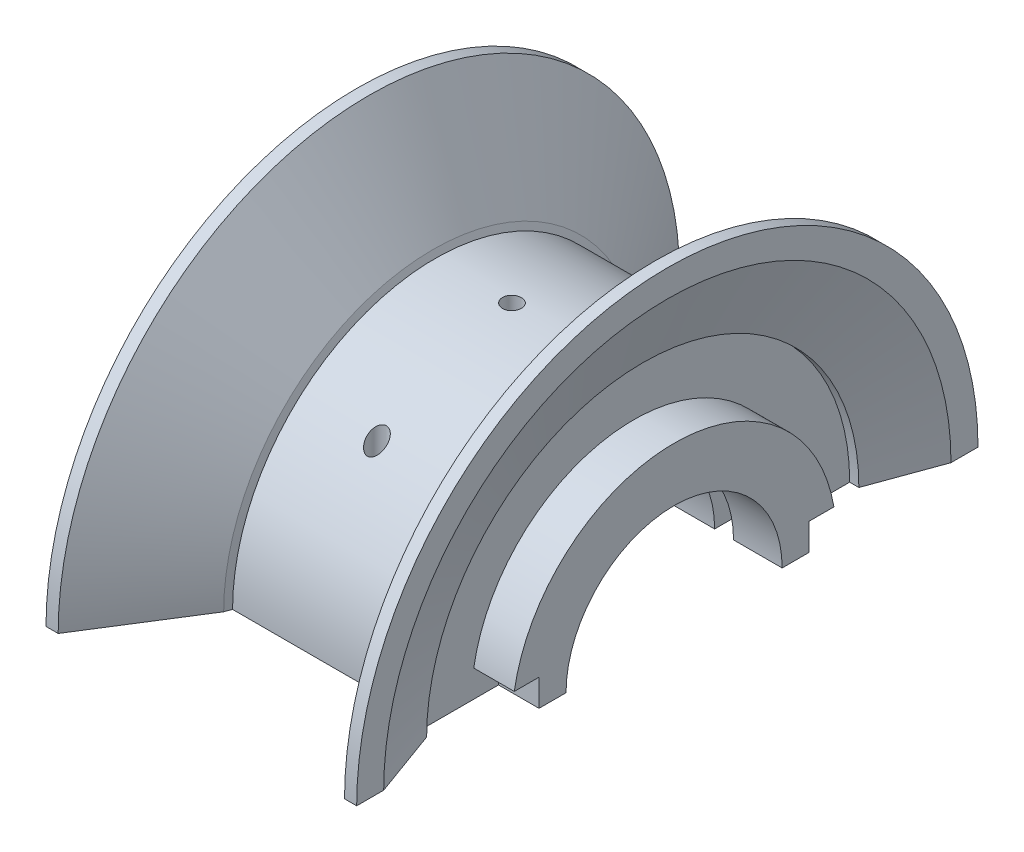
SolidWorks part; units mm, degrees
other "DifferReelB"
material "Nylon 101"
ref_plane "Front" through (0, 0, 0) normal (0, 0, 1) x (1, 0, 0)
ref_plane "Top" through (0, 0, 0) normal (0, 1, 0) x (1, 0, 0)
ref_plane "Right" through (0, 0, 0) normal (1, 0, 0) x (0, 0, -1)
sketch "BodySke" plane through (0, 0, 0) normal (0, 1, 0) x (1, 0, 0)
  line L0 (4.5, 0) -> (4.5, 11.5)
  line L1 (4.5, 11.5) -> (4.3, 11.5)
  line L2 (4.3, 11.5) -> (2.2982, 6)
  line L3 (2.2982, 6) -> (-2.2982, 6)
  line L4 (-2.2982, 6) -> (-4.3, 11.5)
  line L5 (-4.3, 11.5) -> (-4.5, 11.5)
  line L6 (-4.5, 11.5) -> (-4.5, 0)
  line L7 (-4.5, 0) -> (4.5, 0)
  point P2 (0, 0)
  point P9 (0, 6)
  dimension "D1" = 0.2
  dimension "D2" = 6
  dimension "D3" = 70
  dimension "D4" = 11.5
  dimension "D5" = 9
revolve "Body" add sketch "BodySke" angle 360 about L7
sketch "BoldSke" plane through (0, 0, 0) normal (0, 1, 0) x (1, 0, 0)
  line L0 (-2.2982, 6) -> (2.2982, 6)
  line L1 (2.2982, 6) -> (2.8441, 7.5)
  line L2 (4.3, 11.5) -> (2.2982, 6) construction
  line L3 (2.8441, 7.5) -> (-2.8441, 7.5)
  line L4 (-2.2982, 6) -> (-4.3, 11.5) construction
  line L5 (-2.8441, 7.5) -> (-2.2982, 6)
  line L6 (0, 0) -> (10.401, 0) construction
  dimension "D1" = 1.5
revolve "Bold" add sketch "BoldSke" angle 360 about L6
sketch "PadSke" plane through (0, 0, 0) normal (1, 0, 0) x (0, 0, -1)
  circle A0 centre (0, 0) radius 6
  dimension "D1" = 12
extrude "Pad" add sketch "PadSke" along normal mid plane 12
sketch "HoleSke" plane through (0, 0, 0) normal (1, 0, 0) x (0, 0, -1)
  circle A0 centre (0, 0) radius 4
  dimension "D1" = 8
extrude "Hole" cut sketch "HoleSke" against normal through all both and the other way through all
sketch "ScrewHoleSke" plane through (0, 0, 0) normal (0, 1, 0) x (1, 0, 0)
  circle A0 centre (0, 0) radius 0.35
  dimension "D1" = 0.7
extrude "ScrewHole" cut sketch "ScrewHoleSke" against normal through all both and the other way through all
sketch "BoxSke" plane through (0, 0, 0) normal (0, 0, 1) x (1, 0, 0)
  line L1 (-3.5, 4) -> (3.5, 4)
  line L2 (-3.5, 4) -> (-3.5, -4)
  line L3 (-3.5, -4) -> (3.5, -4)
  line L4 (3.5, 4) -> (3.5, -4)
  line L5 (-3.5, 4) -> (3.5, -4) construction
  line L6 (-3.5, -4) -> (3.5, 4) construction
  point P0 (0, 0)
  dimension "D1" = 8
  dimension "D2" = 7
extrude "Box" cut sketch "BoxSke" against normal mid plane 7
sketch "CutSke" plane through (0, 0, 0) normal (0, 1, 0) x (1, 0, 0)
  line L1 (-13, -13) -> (13, -13)
  line L2 (-13, -13) -> (-13, 13)
  line L3 (-13, 13) -> (13, 13)
  line L4 (13, -13) -> (13, 13)
  line L5 (-13, -13) -> (13, 13) construction
  line L6 (-13, 13) -> (13, -13) construction
  point P0 (0, 0)
  dimension "D1" = 26
extrude "Cut" cut sketch "CutSke" against normal blind 20
sketch "ScrewHole2Ske" plane through (0, 0, 0) normal (0, -1, 0) x (1, 0, 0)
  line L0 (0, 6) -> (0, 4) construction
  line L2 (-6, 4) -> (6, 4) construction
  line L3 (0, -4) -> (0, -6) construction
  line L4 (6, -4) -> (-6, -4) construction
  line L7 (-6, -6) -> (6, -6) construction
  line L8 (-6, -6) -> (-6, 6) construction
  line L9 (-6, 6) -> (6, 6) construction
  line L10 (6, -6) -> (6, 6) construction
  line L11 (-6, -6) -> (6, 6) construction
  line L12 (-6, 6) -> (6, -6) construction
  circle A0 centre (0, -5) radius 0.35
  circle A1 centre (0, 0) radius 0.35 construction
  circle A2 centre (0, 5) radius 0.35
  point P4 (0, 0)
  point P8 (0, 5)
  point P21 (0, -5)
extrude "ScrewHole2" cut sketch "ScrewHole2Ske" against normal through all
sketch "SlotSke" plane through (0, 0, 0) normal (0, -1, 0) x (1, 0, 0)
  line L0 (-4.5, 11.5) -> (-4.5, 6) construction
  line L1 (-4.5, 5) -> (-6, 5)
  line L2 (-4.5, 5) -> (-4.5, 6)
  line L3 (-4.5, 6) -> (-6, 6)
  line L4 (-6, 5) -> (-6, 6)
  line L5 (-6, 6) -> (-6, 4) construction
  line L6 (0, -50) -> (0, 50) construction
  line L7 (4.5, 6) -> (6, 6)
  line L8 (6, 5) -> (6, 6)
  line L9 (4.5, 5) -> (6, 5)
  line L10 (4.5, 5) -> (4.5, 6)
  line L11 (50, 0) -> (-50, 0) construction
  line L12 (4.5, -5) -> (4.5, -6)
  line L13 (4.5, -5) -> (6, -5)
  line L14 (6, -5) -> (6, -6)
  line L15 (4.5, -6) -> (6, -6)
  line L16 (-4.5, -6) -> (-6, -6)
  line L17 (-6, -5) -> (-6, -6)
  line L18 (-4.5, -5) -> (-6, -5)
  line L19 (-4.5, -5) -> (-4.5, -6)
  point P10 (-6, 5)
extrude "Slot" cut sketch "SlotSke" against normal blind 1
sketch "FlangeSlotSke" plane through (-3.5, 0, 0) normal (1, 0, 0) x (0, 0, -1)
  circle A0 centre (0, 0) radius 4.65
  dimension "D1" = 9.3
extrude "FlangeSlot" cut sketch "FlangeSlotSke" against normal blind 0.7
mirror "FlangeSlot2" about plane through (0, 0, 0) normal (1, 0, 0) of "FlangeSlot"
sketch "EdgeSke" plane through (0, 0, 0) normal (0, 1, 0) x (1, 0, 0)
  line L0 (4.5, 8) -> (4.8401, 8)
  line L1 (4.5, 0) -> (4.5, 11.5) construction
  line L2 (4.8401, 8) -> (5.75, 10.5)
  line L3 (5.75, 10.5) -> (5.75, 11.5)
  line L4 (5.75, 11.5) -> (4.5, 11.5)
  line L5 (4.5, 11.5) -> (4.5, 8)
  line L7 (2.8441, 7.5) -> (2.9319, 7.7412) construction
  line L8 (6, -5.9161) -> (6, 5.9161) construction
  line L9 (0, -50) -> (0, 50) construction
  line L10 (-5.75, 11.5) -> (-4.5, 11.5)
  line L11 (-5.75, 10.5) -> (-5.75, 11.5)
  line L12 (-4.8401, 8) -> (-5.75, 10.5)
  line L13 (-4.5, 8) -> (-4.8401, 8)
  line L14 (-4.5, 11.5) -> (-4.5, 8)
  dimension "D1" = 1
  dimension "D2" = 0.25
  dimension "D3" = 8
revolve "Edge" add sketch "EdgeSke" angle 180 about L7
chamfer "Chamfer" distance 1 distance2 4 1 edges at (4.3, 11.5, 0)
chamfer "Chamfer2" distance 4 distance2 1 1 edges at (-4.3, 11.5, 0)
